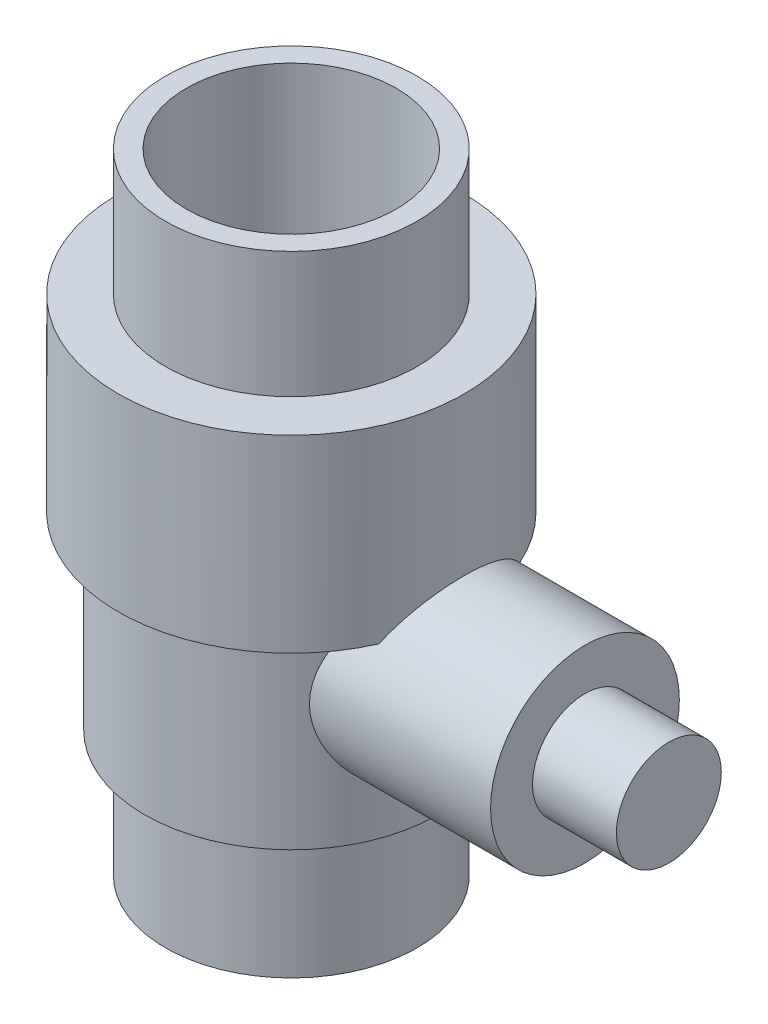
SolidWorks part; units mm, degrees
ref_plane "Front" through (0, 0, 0) normal (0, 0, 1) x (1, 0, 0)
ref_plane "Top" through (0, 0, 0) normal (0, 1, 0) x (1, 0, 0)
ref_plane "Right" through (0, 0, 0) normal (1, 0, 0) x (0, 0, -1)
sketch "Sketch1" plane through (0, 0, 0) normal (0, 1, 0) x (1, 0, 0)
  circle A0 centre (0, 0) radius 10.4775
extrude "Boss-Extrude1" add sketch "Sketch1" along normal blind 11.43
sketch "Sketch2" plane through (0, 0, 0) normal (0, -1, 0) x (1, 0, 0)
  circle A0 centre (0, 0) radius 8.89
extrude "Boss-Extrude2" add sketch "Sketch2" along normal blind 11.43
sketch "Sketch3" plane through (0, -11.43, 0) normal (0, -1, 0) x (1, 0, 0)
  circle A0 centre (0, 0) radius 7.62
extrude "Boss-Extrude3" add sketch "Sketch3" along normal blind 7.62 and the other way blind 30.48
sketch "Sketch4" plane through (0, 0, 0) normal (1, 0, 0) x (0, 0, -1)
  line L0 (0, 0) -> (0, -3.81)
  circle A0 centre (0, -3.81) radius 5.715
extrude "Boss-Extrude4" add sketch "Sketch4" along normal blind 17.78
sketch "Sketch5" plane through (17.78, 0, 0) normal (1, 0, 0) x (0, 0, -1)
  circle A0 centre (0, -3.81) radius 3.175
extrude "Boss-Extrude5" add sketch "Sketch5" along normal blind 5.08
sketch "Sketch6" plane through (0, 19.05, 0) normal (0, 1, 0) x (1, 0, 0)
  circle A0 centre (0, 0) radius 6.35
extrude "Cut-Extrude1" cut sketch "Sketch6" against normal through all
